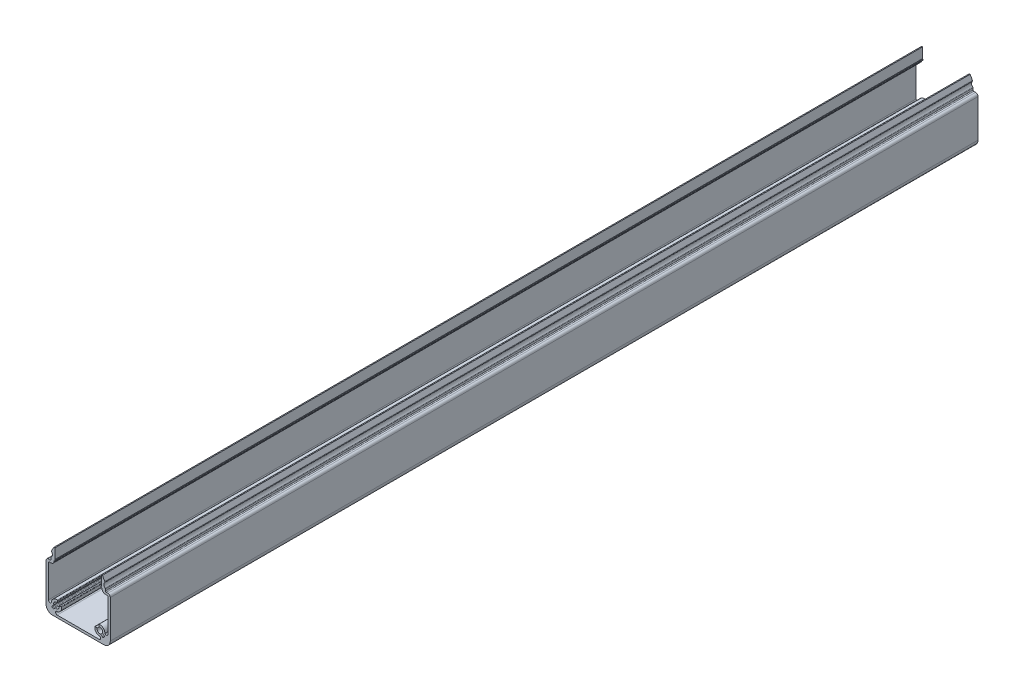
SolidWorks part; units mm, degrees
ref_plane "Front Plane" through (0, 0, 0) normal (0, 0, 1) x (1, 0, 0)
ref_plane "Top Plane" through (0, 0, 0) normal (0, 1, 0) x (1, 0, 0)
ref_plane "Right Plane" through (0, 0, 0) normal (1, 0, 0) x (0, 0, -1)
ref_plane "Plane1" through (0, 0, 20) normal (0, 0, 1) x (1, 0, 0)
sketch "Sketch1" plane through (0, 0, 20) normal (0, 0, 1) x (1, 0, 0)
  line L0 (4, 0) -> (36, 0)
  line L1 (40, 4) -> (40, 27.5)
  line L2 (38.5, 29) -> (37.4085, 29)
  line L3 (36.9085, 29.5) -> (36.9085, 30.572)
  line L4 (36.583, 34.4315) -> (35.1, 37)
  line L5 (35.1, 37) -> (34.5, 37)
  line L6 (34.5, 37) -> (34.5, 30.6727)
  line L7 (34.5, 30.6727) -> (34.1585, 30.5611)
  line L8 (34.1585, 30.5611) -> (34.1585, 29.9899)
  line L9 (34.1585, 29.9899) -> (34.9085, 29.9899)
  line L10 (34.9085, 29.9899) -> (34.9085, 29.7)
  line L11 (36.9085, 27.7) -> (38, 27.7)
  line L12 (38.5, 27.2) -> (38.5, 6.9548)
  line L13 (36.7929, 6.2477) -> (36.6482, 6.3924)
  line L14 (32.7665, 9.2376) -> (33.0471, 8.1904)
  line L15 (35.1484, 5.9123) -> (36.1464, 4.9142)
  line L16 (36.1464, 4.2071) -> (35.7929, 3.8536)
  line L17 (35.0858, 3.8536) -> (34.0877, 4.8516)
  line L18 (31.8096, 6.9529) -> (30.7624, 7.2335)
  line L19 (33.6076, 3.3518) -> (33.7523, 3.2071)
  line L20 (33.0452, 1.5) -> (6.9548, 1.5)
  line L21 (6.2477, 3.2071) -> (6.3924, 3.3518)
  line L22 (9.2376, 7.2335) -> (8.1904, 6.9529)
  line L23 (5.9123, 4.8516) -> (4.9142, 3.8536)
  line L24 (4.2071, 3.8536) -> (3.8536, 4.2071)
  line L25 (3.8536, 4.9142) -> (4.8516, 5.9123)
  line L26 (6.9529, 8.1904) -> (7.2335, 9.2376)
  line L27 (3.3518, 6.3924) -> (3.2071, 6.2477)
  line L28 (1.5, 6.9548) -> (1.5, 27.2)
  line L29 (2, 27.7) -> (3.0915, 27.7)
  line L30 (5.0915, 29.7) -> (5.0915, 29.9899)
  line L31 (5.0915, 29.9899) -> (5.8415, 29.9899)
  line L32 (5.8415, 29.9899) -> (5.8415, 30.5611)
  line L33 (5.8415, 30.5611) -> (5.5, 30.6727)
  line L34 (5.5, 30.6727) -> (5.5, 37)
  line L35 (5.5, 37) -> (4.9, 37)
  line L36 (4.9, 37) -> (3.417, 34.4315)
  line L37 (3.0915, 30.572) -> (3.0915, 29.5)
  line L38 (2.5915, 29) -> (1.5, 29)
  line L39 (0, 27.5) -> (0, 4)
  arc A0 (36, 0) -> (40, 4) centre (36, 4) ccw
  arc A1 (40, 27.5) -> (38.5, 29) centre (38.5, 27.5) ccw
  arc A2 (37.4085, 29) -> (36.9085, 29.5) centre (37.4085, 29.5) cw
  arc A3 (36.9085, 30.572) -> (36.7268, 30.9576) centre (36.4085, 30.572) ccw
  arc A4 (36.7268, 30.9576) -> (36.52, 33.8452) centre (38, 32.5) cw
  arc A5 (36.52, 33.8452) -> (36.583, 34.4315) centre (36.1499, 34.1815) ccw
  arc A6 (34.9085, 29.7) -> (36.9085, 27.7) centre (36.9085, 29.7) ccw
  arc A7 (38, 27.7) -> (38.5, 27.2) centre (38, 27.2) cw
  arc A8 (38.5, 6.9548) -> (36.7929, 6.2477) centre (37.5, 6.9548) cw
  arc A9 (36.6482, 6.3924) -> (33.0095, 9.6116) centre (33.5, 6.5) ccw
  arc A10 (33.0095, 9.6116) -> (32.7665, 9.2376) centre (33.0562, 9.3152) ccw
  arc A11 (33.0471, 8.1904) -> (35.1484, 5.9123) centre (33.5, 6.5) cw
  arc A12 (36.1464, 4.9142) -> (36.1464, 4.2071) centre (35.7929, 4.5607) cw
  arc A13 (35.7929, 3.8536) -> (35.0858, 3.8536) centre (35.4393, 4.2071) cw
  arc A14 (34.0877, 4.8516) -> (31.8096, 6.9529) centre (33.5, 6.5) cw
  arc A15 (30.7624, 7.2335) -> (30.3884, 6.9905) centre (30.6848, 6.9438) ccw
  arc A16 (30.3884, 6.9905) -> (33.6076, 3.3518) centre (33.5, 6.5) ccw
  arc A17 (33.7523, 3.2071) -> (33.0452, 1.5) centre (33.0452, 2.5) cw
  arc A18 (6.9548, 1.5) -> (6.2477, 3.2071) centre (6.9548, 2.5) cw
  arc A19 (6.3924, 3.3518) -> (9.6116, 6.9905) centre (6.5, 6.5) ccw
  arc A20 (9.6116, 6.9905) -> (9.2376, 7.2335) centre (9.3152, 6.9438) ccw
  arc A21 (8.1904, 6.9529) -> (5.9123, 4.8516) centre (6.5, 6.5) cw
  arc A22 (4.9142, 3.8536) -> (4.2071, 3.8536) centre (4.5607, 4.2071) cw
  arc A23 (3.8536, 4.2071) -> (3.8536, 4.9142) centre (4.2071, 4.5607) cw
  arc A24 (4.8516, 5.9123) -> (6.9529, 8.1904) centre (6.5, 6.5) cw
  arc A25 (7.2335, 9.2376) -> (6.9905, 9.6116) centre (6.9438, 9.3152) ccw
  arc A26 (6.9905, 9.6116) -> (3.3518, 6.3924) centre (6.5, 6.5) ccw
  arc A27 (3.2071, 6.2477) -> (1.5, 6.9548) centre (2.5, 6.9548) cw
  arc A28 (1.5, 27.2) -> (2, 27.7) centre (2, 27.2) cw
  arc A29 (3.0915, 27.7) -> (5.0915, 29.7) centre (3.0915, 29.7) ccw
  arc A30 (3.417, 34.4315) -> (3.48, 33.8452) centre (3.8501, 34.1815) ccw
  arc A31 (3.48, 33.8452) -> (3.2732, 30.9576) centre (2, 32.5) cw
  arc A32 (3.2732, 30.9576) -> (3.0915, 30.572) centre (3.5915, 30.572) ccw
  arc A33 (3.0915, 29.5) -> (2.5915, 29) centre (2.5915, 29.5) cw
  arc A34 (1.5, 29) -> (0, 27.5) centre (1.5, 27.5) ccw
  arc A35 (0, 4) -> (4, 0) centre (4, 4) ccw
extrude "Boss-Extrude1" add sketch "Sketch1" against normal blind 540
